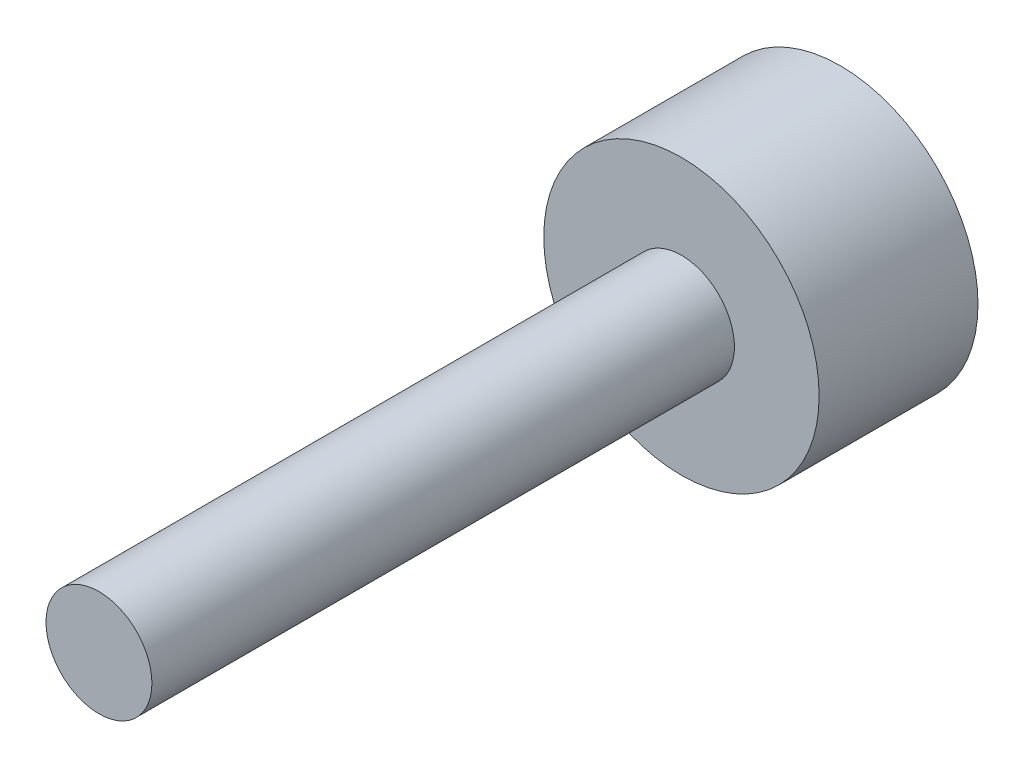
SolidWorks part; units mm, degrees
ref_plane "Front Plane" through (0, 0, 0) normal (0, 0, 1) x (1, 0, 0)
ref_plane "Top Plane" through (0, 0, 0) normal (0, 1, 0) x (1, 0, 0)
ref_plane "Right Plane" through (0, 0, 0) normal (1, 0, 0) x (0, 0, -1)
sketch "Sketch1" plane through (0, 0, 0) normal (0, 0, 1) x (1, 0, 0)
  circle A0 centre (0, 0) radius 5
  dimension "D1" = 10
extrude "Boss-Extrude1" add sketch "Sketch1" along normal blind 60
ref_plane "Plane1" through (0, 0, 5) normal (0, 0, -1) x (-1, 0, 0)
sketch "Sketch2" plane through (0, 0, 5) normal (0, 0, -1) x (-1, 0, 0)
  circle A0 centre (0, 0) radius 13
  dimension "D1" = 26
extrude "Boss-Extrude2" add sketch "Sketch2" along normal blind 15
sketch "Sketch3" plane through (0, 0, -10) normal (0, 0, -1) x (-1, 0, 0)
  circle A0 centre (0, 0) radius 5
  dimension "D1" = 10
extrude "Cut-Extrude2" cut sketch "Sketch3" against normal blind 10 contours A0
